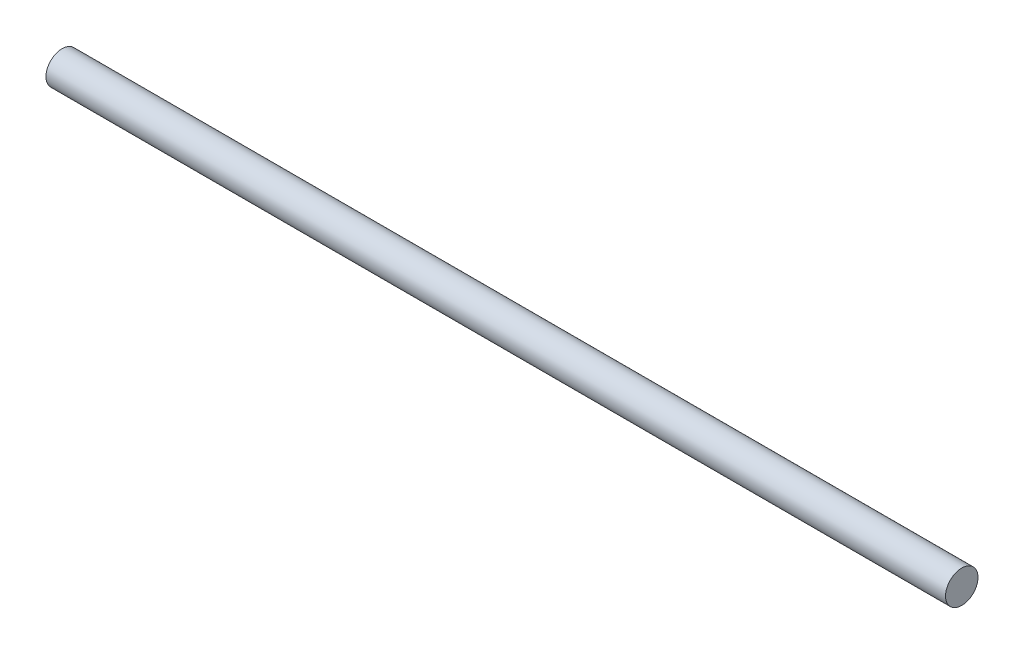
SolidWorks part; units mm, degrees
ref_plane "Front Plane" through (0, 0, 0) normal (0, 0, 1) x (1, 0, 0)
ref_plane "Top Plane" through (0, 0, 0) normal (0, 1, 0) x (1, 0, 0)
ref_plane "Right Plane" through (0, 0, 0) normal (1, 0, 0) x (0, 0, -1)
sketch "Sketch1" plane through (0, 0, 0) normal (1, 0, 0) x (0, 0, -1)
  circle A0 centre (0, 0) radius 21.082
  dimension "D1" = 42.164
extrude "Boss-Extrude1" add sketch "Sketch1" along normal blind 1168.4
